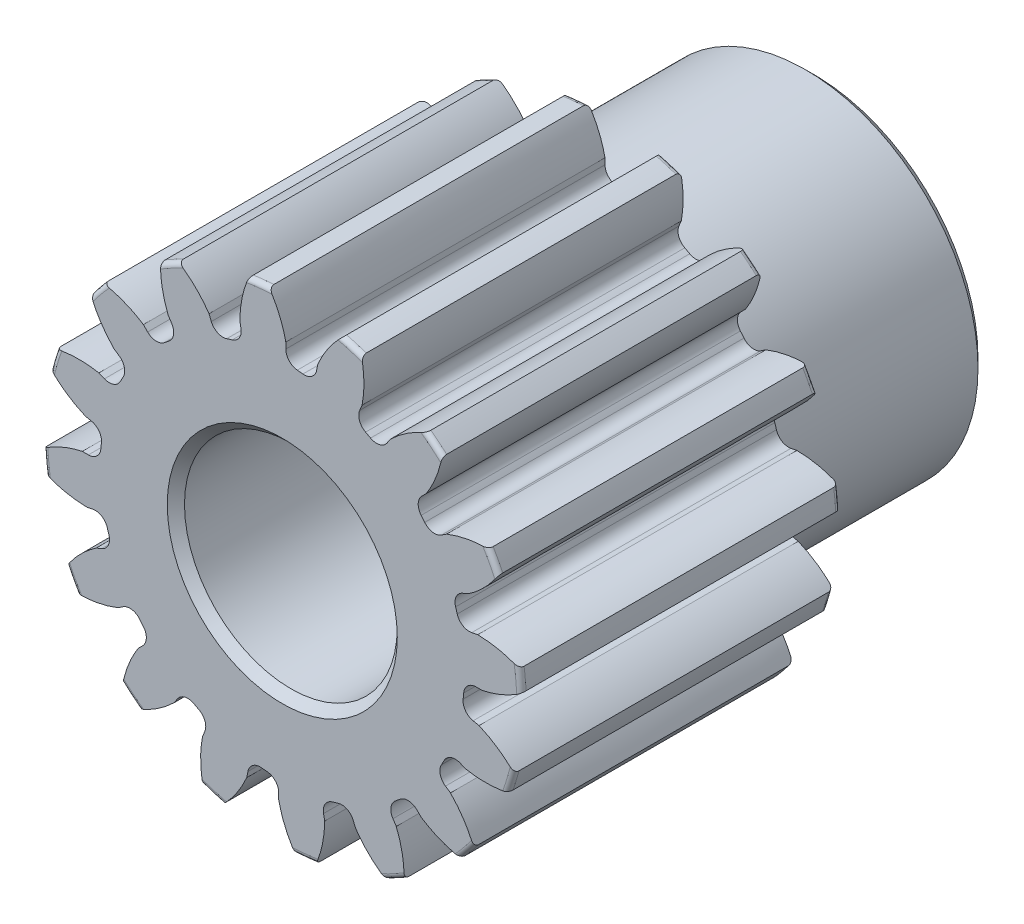
SolidWorks part; units mm, degrees
ref_plane "Front" through (0, 0, 0) normal (0, 0, 1) x (1, 0, 0)
ref_plane "Top" through (0, 0, 0) normal (0, 1, 0) x (1, 0, 0)
ref_plane "Right" through (0, 0, 0) normal (1, 0, 0) x (0, 0, -1)
sketch "Sketch1" plane through (0, 0, 0) normal (0, 0, 1) x (1, 0, 0)
  line L0 (-203.2, 0) -> (203.2, 0) construction
  circle A0 centre (0, 0) radius 14.2875
  circle A1 centre (0, 0) radius 12.7 construction
  circle A3 centre (0, 0) radius 10.8633 construction
  dimension "D1" = 1.8367
  dimension "D2" = 3.4242
  dimension "D3" = 1.5875
extrude "Boss-Extrude1" add sketch "Sketch1" against normal blind 19.05
sketch "Sketch2" plane through (0, 0, 0) normal (1, 0, 0) x (0, 0, -1)
  line L0 (19.05, 0) -> (31.75, 0)
  line L1 (19.05, 0) -> (19.05, 10.287)
  line L2 (19.05, 10.287) -> (31.75, 10.287)
  line L3 (31.75, 10.287) -> (31.75, 0)
  point P5 (31.75, -10.287)
  point P6 (0, -14.2875)
  point P7 (19.05, -14.2875)
  point P9 (0, 14.2875)
revolve "Revolve1" add sketch "Sketch2" angle 360 mid plane about L0
fillet "Fillet2" radius 0.2858 3 edges at (14.2875, 0, -19.05) (14.2875, 0, 0) (10.287, 0, -19.05)
sketch "Sketch3" plane through (0, 0, 0) normal (0, 0, 1) x (1, 0, 0)
  line L0 (0, 0) -> (0, 14.2875) construction
  line L1 (-4.0817, 11.2144) -> (0, 12.7)
  line L2 (-9.5921, 12.7) -> (9.5921, 12.7) construction
  line L3 (-9.0136, 9.4193) -> (9.0136, 15.9807) construction
  line L4 (-4.0817, 11.2144) -> (0, 0) construction
  line L5 (-9.951, 6.5878) -> (0, 0) construction
  line L6 (-9.951, 6.5878) -> (-3.3571, 16.548) construction
  line L7 (-2.8353, 11.5924) -> (0, 0) construction
  line L8 (-2.8353, 11.5924) -> (0.1182, 12.3148) construction
  arc A0 (-4.0817, 11.2144) -> (-9.951, 6.5878) centre (0, 0) ccw
  circle A1 centre (0, 0) radius 12.7 construction
  circle A2 centre (0, 0) radius 11.9341 construction
  arc A3 (-4.0817, 11.2144) -> (-2.8353, 11.5924) centre (0, 0) cw
  circle A4 centre (0, 0) radius 14.2875 construction
  point P6 (0, 12.7)
  dimension "D1" = 4.3437
  dimension "D3" = 11.9451
  dimension "D5" = 3.0406
  dimension "D2" = 7.6014
  dimension "D4" = 1.3031
sketch "Sketch4" plane through (0, 0, 0) normal (0, 0, 1) x (1, 0, 0)
  line L0 (0, 0) -> (1.2388, 12.578) construction
  line L1 (0.2108, 11.9322) -> (0.2108, 10.8612)
  line L2 (0, 12.7) -> (2.4777, 12.456) construction
  line L3 (2.1211, 11.7441) -> (1.9122, 10.6937)
  line L4 (0.2108, 10.8612) -> (0, 0) construction
  line L5 (0, 0) -> (0, 14.2875) construction
  line L6 (-9.951, 6.5878) -> (-3.3571, 16.548) construction
  line L7 (-9.951, 6.5878) -> (-3.3571, 16.548) construction
  arc A0 (1.9122, 10.6937) -> (0.2108, 10.8612) centre (0, 0) ccw
  arc A1 (0, 12.7) -> (2.4777, 12.456) centre (0, 0) cw construction
  circle A2 centre (0, 0) radius 12.7 construction
  circle A3 centre (0, 0) radius 11.9341 construction
  circle A4 centre (0, 0) radius 10.8633 construction
  arc A5 (6.521, 15.5751) -> (-3.3571, 16.548) centre (0, 0) ccw
  spline S0 degree 2 poles (-3.3571, 16.548) (-0.4015, 14.8243) (0.2108, 11.9322) knots 0 0 0 1 1 1
  spline S1 degree 2 poles (6.521, 15.5751) (3.2858, 14.4611) (2.1211, 11.7441) knots 0 0 0 1 1 1
  dimension "D1" = 2.4936
extrude "Cut-Extrude1" cut sketch "Sketch4" against normal through all
fillet "Fillet1" radius 0.7481 2 edges at (1.9122, 10.6937, -9.525) (0.2108, 10.8612, -9.525)
pattern_circular "CirPattern1" count 16 over 360 about axis through (0, 0, -19.05) along (0, 0, 1) of "Cut-Extrude1", "Fillet1"
sketch "Sketch5" plane through (0, 0, 0) normal (0, 0, 1) x (1, 0, 0)
  circle A0 centre (0, 0) radius 6.35
  circle A1 centre (0, 0) radius 6.35 construction
  dimension "Bore Min" = 12.7
  dimension "Bore Max" = 12.7
extrude "Cut-Extrude2" cut sketch "Sketch5" against normal through all
chamfer "Chamfer1" distance 0.5144 angle 45 3 edges at (10.287, 0, -31.75) (6.35, 0, 0) (6.35, 0, -31.75)
sketch "Pitch Dia" plane through (0, 0, 0) normal (0, 0, 1) x (1, 0, 0)
  circle A0 centre (0, 0) radius 12.7 construction
  circle A1 centre (0, 0) radius 12.7 construction
equation "\"D1@Boss-Extrude1\" = \"Face Wd@Sketch2\""
equation "\"D2@Sketch3\" = \"D1@Sketch3\"*1.75"
equation "\"D3@Sketch3\" = \"D1@Sketch3\"+\"D2@Sketch3\""
equation "\"D4@Sketch3\" = \"D1@Sketch3\"*.3"
equation "\"D5@Sketch3\" = \"D1@Sketch3\"-\"D4@Sketch3\""
equation "\"D1@Sketch4\" = 1.5708/(\"Number of Teeth@Sketch1\"/\"Ptich Dia@Sketch1\")"
equation "\"D1@Chamfer1\" = \"B Hub Dia@Sketch2\"*.025"
equation "\"D1@CirPattern1\" = \"Number of Teeth@Sketch1\""
equation "\"D1@Fillet1\" = \"D1@Sketch4\"*.3"
equation "\"D1@Fillet2\" = \"OD@Sketch1\"*.01"
equation "\"D1@Sketch1\" = 1.157/(\"Number of Teeth@Sketch1\"/\"Ptich Dia@Sketch1\")"
